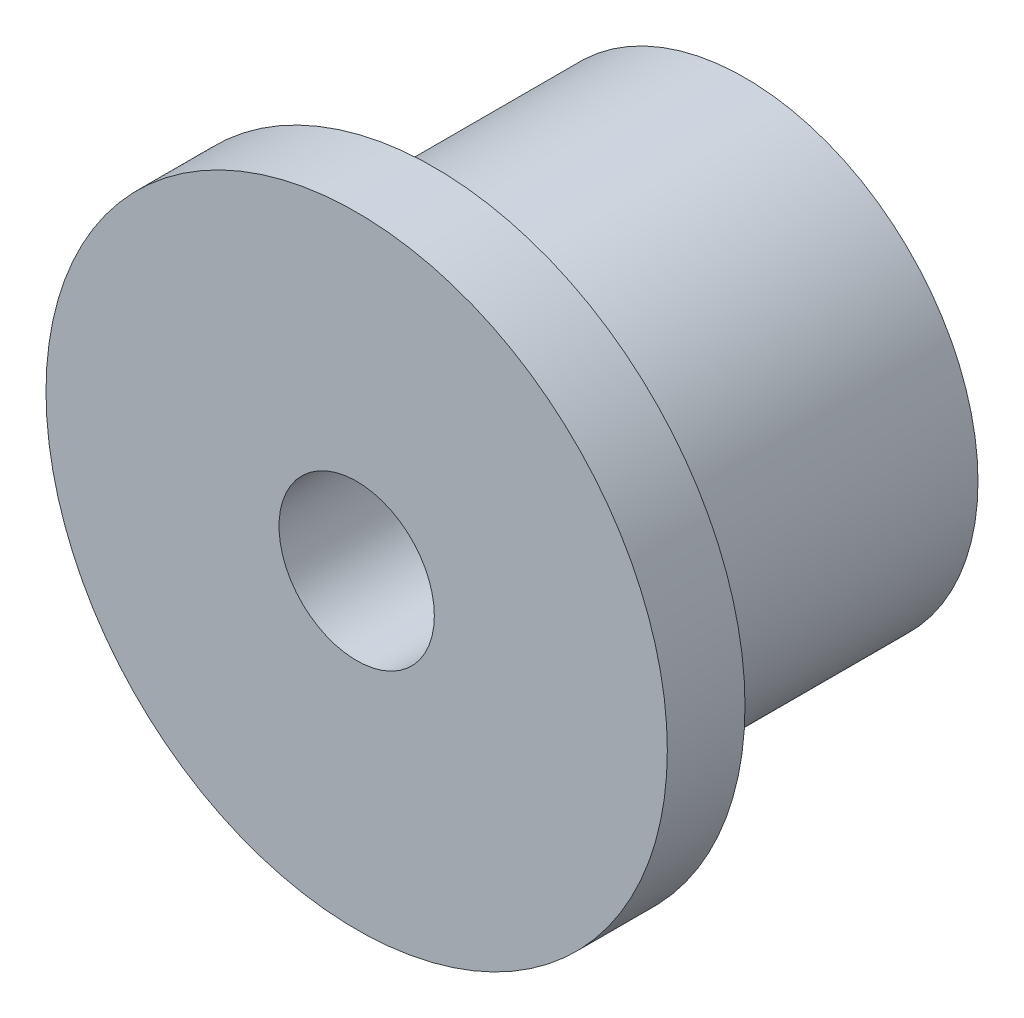
SolidWorks part; units mm, degrees
material "Commercial Bronze, UNS C22000 (90-10 Bronze)"
ref_plane "Front Plane" through (0, 0, 0) normal (0, 0, 1) x (1, 0, 0)
ref_plane "Top Plane" through (0, 0, 0) normal (0, 1, 0) x (1, 0, 0)
ref_plane "Right Plane" through (0, 0, 0) normal (1, 0, 0) x (0, 0, -1)
sketch "Sketch1" plane through (0, 0, 0) normal (0, 0, 1) x (1, 0, 0)
  circle A0 centre (0, 0) radius 25.4
  dimension "D1" = 50.8
extrude "Boss-Extrude2" add sketch "Sketch1" against normal blind 6.35 contours A0
sketch "Sketch2" plane through (0, 0, -6.35) normal (0, 0, -1) x (-1, 0, 0)
  circle A0 centre (0, 0) radius 19.05
extrude "Boss-Extrude3" add sketch "Sketch2" along normal blind 25.4 contours A0
sketch "Sketch3" plane through (0, 0, 0) normal (0, 0, 1) x (1, 0, 0)
  circle A0 centre (0, 0) radius 6.35
  dimension "D1" = 12.7
extrude "Cut-Extrude2" cut sketch "Sketch3" against normal through all contours A0
